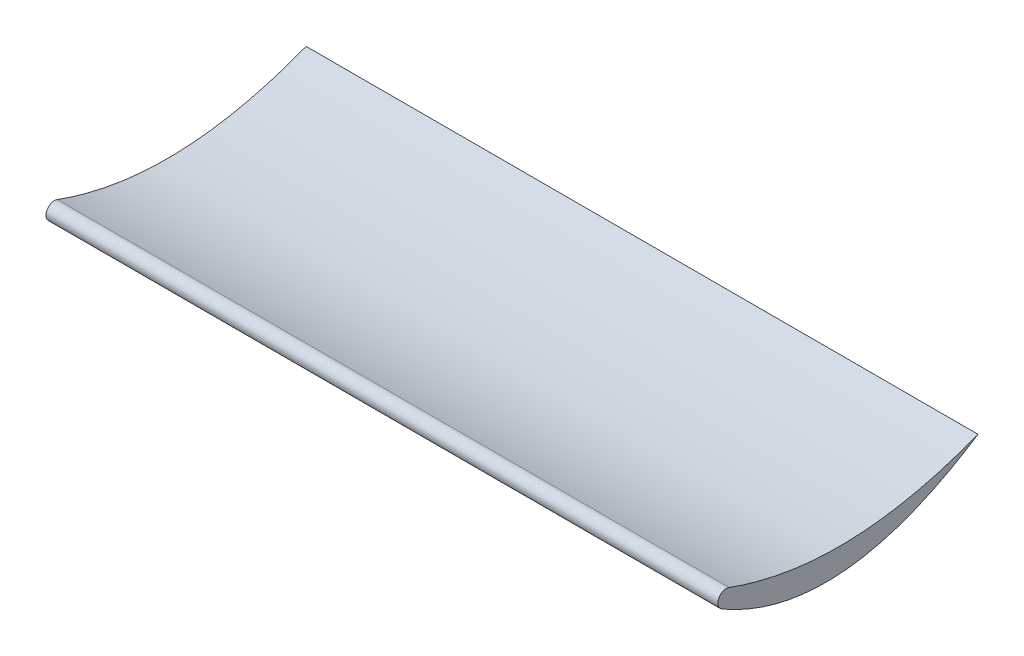
SolidWorks part; units mm, degrees
ref_plane "Front Plane" through (0, 0, 0) normal (0, 0, 1) x (1, 0, 0)
ref_plane "Top Plane" through (0, 0, 0) normal (0, 1, 0) x (1, 0, 0)
ref_plane "Right Plane" through (0, 0, 0) normal (1, 0, 0) x (0, 0, -1)
sketch "Sketch1" plane through (0, 0, 0) normal (1, 0, 0) x (0, 0, -1)
  spline S0 degree 2 poles (-228.0884, 62.6242) (-11.7118, -156.9775) (257.674, 20.0403) knots 0 0 0 1 1 1
  spline S1 degree 2 poles (-228.0884, 62.6242) (-4.2627, -81.7597) (257.674, 20.0403) knots 0 0 0 1 1 1
  point P0 (-228.0884, 62.6242)
  point P1 (257.674, 20.0403)
  dimension "D1" = 508
extrude "Boss-Extrude1" add sketch "Sketch1" along normal blind 1016
fillet "Fillet1" radius 12.7 1 edges at (508, 62.6242, 228.0884)
